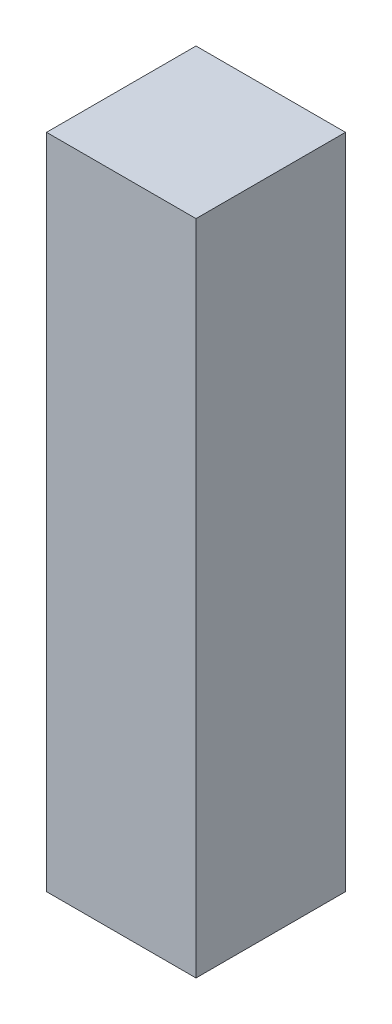
SolidWorks part; units mm, degrees
ref_plane "Ebene vorne" through (0, 0, 0) normal (0, 0, 1) x (1, 0, 0)
ref_plane "Ebene oben" through (0, 0, 0) normal (0, 1, 0) x (1, 0, 0)
ref_plane "Ebene rechts" through (0, 0, 0) normal (1, 0, 0) x (0, 0, -1)
sketch "Skizze2" plane through (0, 0, 0) normal (0, 1, 0) x (1, 0, 0)
  line L1 (100, 100) -> (-100, 100)
  line L2 (100, 100) -> (100, -100)
  line L3 (100, -100) -> (-100, -100)
  line L4 (-100, 100) -> (-100, -100)
  line L5 (100, 100) -> (-100, -100) construction
  line L6 (100, -100) -> (-100, 100) construction
  point P0 (0, 0)
  dimension "D1" = 200
  dimension "D2" = 200
extrude "Aufsatz-Linear austragen1" add sketch "Skizze2" along normal blind 880
